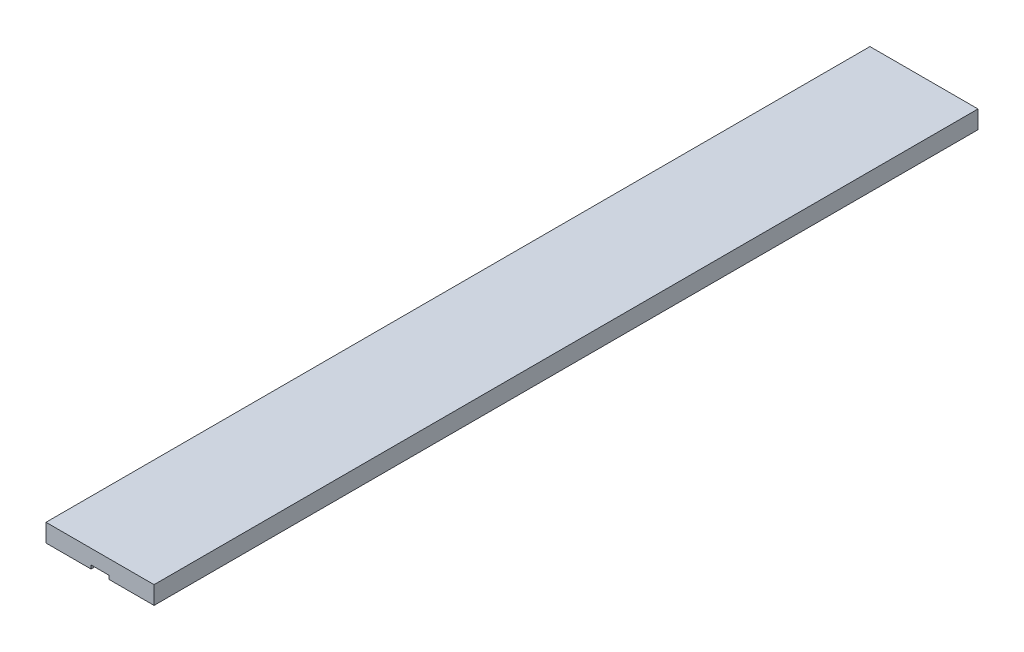
SolidWorks part; units mm, degrees
ref_plane "前视基准面" through (0, 0, 0) normal (0, 0, 1) x (1, 0, 0)
ref_plane "上视基准面" through (0, 0, 0) normal (0, 1, 0) x (1, 0, 0)
ref_plane "右视基准面" through (0, 0, 0) normal (1, 0, 0) x (0, 0, -1)
sketch "草图1" plane through (0, 0, 0) normal (0, 1, 0) x (1, 0, 0)
  line L0 (-119.5234, 0) -> (105.4611, 0) construction
  line L1 (0, -124.251) -> (0, 139.2842) construction
  line L2 (-81.9778, 0) -> (-81.9778, -228.76)
  line L3 (-81.9778, -228.76) -> (-51.9778, -228.76)
  line L4 (-51.9778, -228.76) -> (-51.9778, 0)
  line L5 (-51.9778, 0) -> (-81.9778, 0)
extrude "凸台-拉伸1" add sketch "草图1" along normal blind 5
sketch "草图2" plane through (0, 0, 0) normal (0, -1, 0) x (1, 0, 0)
  line L0 (-69.4778, 228.76) -> (-64.4778, 228.76)
  line L1 (-81.9778, 228.76) -> (-51.9778, 228.76) construction
  line L2 (-69.4778, 228.76) -> (-69.4778, 0)
  line L3 (-51.9778, 0) -> (-81.9778, 0) construction
  line L4 (-69.4778, 0) -> (-64.4778, 0)
  line L5 (-81.9778, 0) -> (-81.9778, 228.76) construction
  line L6 (-64.4778, 228.76) -> (-64.4778, 0)
  dimension "D1" = 5
  dimension "D2" = 12.5
extrude "切除-拉伸1" cut sketch "草图2" against normal blind 1
